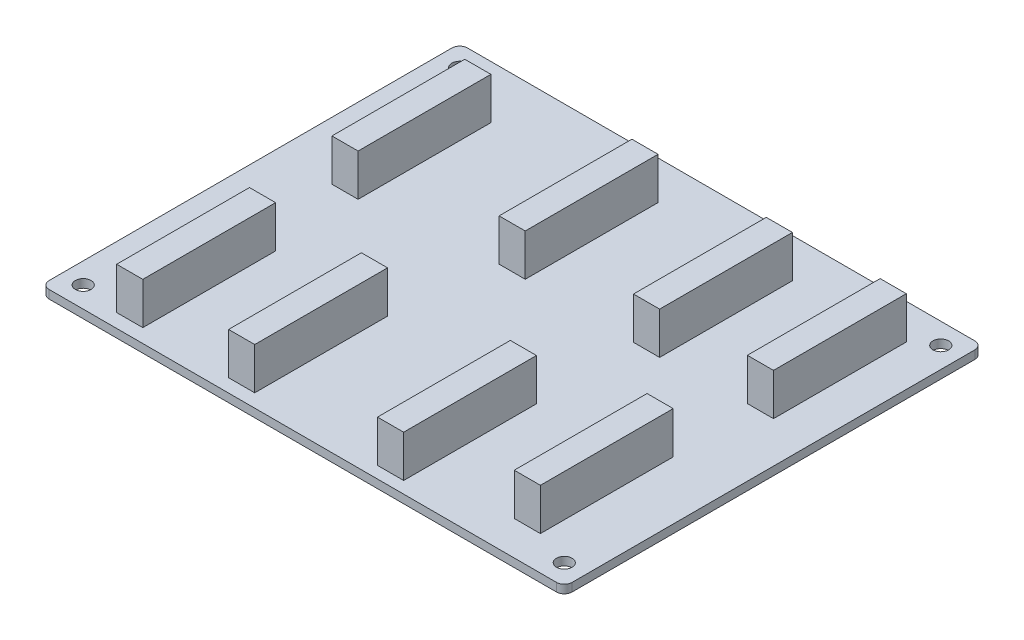
SolidWorks part; units mm, degrees
ref_plane "Front Plane" through (0, 0, 0) normal (0, 0, 1) x (1, 0, 0)
ref_plane "Top Plane" through (0, 0, 0) normal (0, 1, 0) x (1, 0, 0)
ref_plane "Right Plane" through (0, 0, 0) normal (1, 0, 0) x (0, 0, -1)
sketch "Sketch1" plane through (0, 0, 0) normal (0, 1, 0) x (1, 0, 0)
  line L1 (1.5, 0) -> (98.5, 0)
  line L2 (0, 1.5) -> (0, 78.5)
  line L3 (1.5, 80) -> (98.5, 80)
  line L4 (100, 1.5) -> (100, 78.5)
  arc A0 (1.5, 0) -> (0, 1.5) centre (1.5, 1.5) cw
  arc A1 (98.5, 0) -> (100, 1.5) centre (98.5, 1.5) ccw
  arc A2 (98.5, 80) -> (100, 78.5) centre (98.5, 78.5) cw
  arc A3 (0, 78.5) -> (1.5, 80) centre (1.5, 78.5) cw
  circle A4 centre (4, 4) radius 1.5
  circle A6 centre (96, 76) radius 1.5
  circle A7 centre (96, 4) radius 1.5
  circle A8 centre (4, 76) radius 1.5
  point P7 (0, 0)
  point P12 (100, 80)
  point P15 (0, 80)
  dimension "D3" = 1.5
  dimension "D4" = 4
  dimension "D6" = 3
  dimension "D1" = 100
  dimension "D2" = 80
  dimension "D5" = 4
  dimension "D7" = 4
  dimension "D8" = 4
extrude "Boss-Extrude1" add sketch "Sketch1" along normal blind 1.6
sketch "Sketch2" plane through (0, 1.6, 0) normal (0, 1, 0) x (1, 0, 0)
  line L0 (11.7618, 28.0321) -> (16.7618, 28.0321)
  line L1 (11.0975, 69.87) -> (16.0975, 69.87)
  line L2 (11.0975, 69.87) -> (11.0975, 44.47)
  line L3 (11.0975, 44.47) -> (16.0975, 44.47)
  line L4 (16.0975, 69.87) -> (16.0975, 44.47)
  line L5 (11.7618, 28.0321) -> (11.7618, 2.6321)
  line L6 (11.7618, 2.6321) -> (16.7618, 2.6321)
  line L7 (16.7618, 28.0321) -> (16.7618, 2.6321)
  line L8 (87.147, 73.2632) -> (92.147, 73.2632)
  line L9 (87.147, 73.2632) -> (87.147, 47.8632)
  line L10 (87.147, 47.8632) -> (92.147, 47.8632)
  line L11 (92.147, 73.2632) -> (92.147, 47.8632)
  line L12 (83.8896, 31.941) -> (88.8896, 31.941)
  line L13 (83.8896, 31.941) -> (83.8896, 6.541)
  line L14 (83.8896, 6.541) -> (88.8896, 6.541)
  line L15 (88.8896, 31.941) -> (88.8896, 6.541)
  line L16 (40.3209, 72.6118) -> (45.3209, 72.6118)
  line L17 (40.3209, 72.6118) -> (40.3209, 47.2118)
  line L18 (40.3209, 47.2118) -> (45.3209, 47.2118)
  line L19 (45.3209, 72.6118) -> (45.3209, 47.2118)
  line L20 (66.1136, 72.5187) -> (71.1136, 72.5187)
  line L21 (66.1136, 72.5187) -> (66.1136, 47.1187)
  line L22 (66.1136, 47.1187) -> (71.1136, 47.1187)
  line L23 (71.1136, 72.5187) -> (71.1136, 47.1187)
  line L24 (33.2606, 27.939) -> (38.2606, 27.939)
  line L25 (33.2606, 27.939) -> (33.2606, 2.539)
  line L26 (33.2606, 2.539) -> (38.2606, 2.539)
  line L27 (38.2606, 27.939) -> (38.2606, 2.539)
  line L28 (62.0186, 27.6598) -> (67.0186, 27.6598)
  line L29 (62.0186, 27.6598) -> (62.0186, 2.2598)
  line L30 (62.0186, 2.2598) -> (67.0186, 2.2598)
  line L31 (67.0186, 27.6598) -> (67.0186, 2.2598)
  dimension "D1" = 5
  dimension "D2" = 25.4
  dimension "D3" = 25.4
  dimension "D4" = 25.4
  dimension "D5" = 25.4
  dimension "D6" = 25.4
  dimension "D7" = 25.4
  dimension "D8" = 25.4
  dimension "D9" = 25.4
extrude "Boss-Extrude2" add sketch "Sketch2" along normal blind 8
